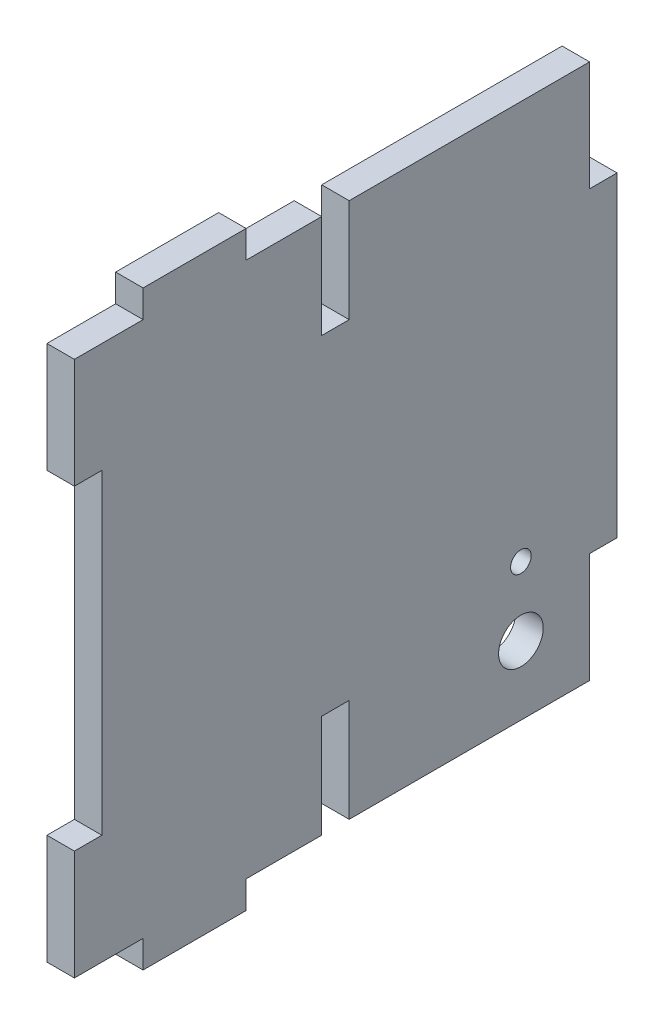
SolidWorks part; units mm, degrees
ref_plane "Front Plane" through (0, 0, 0) normal (0, 0, 1) x (1, 0, 0)
ref_plane "Top Plane" through (0, 0, 0) normal (0, 1, 0) x (1, 0, 0)
ref_plane "Right Plane" through (0, 0, 0) normal (1, 0, 0) x (0, 0, -1)
sketch "Sketch1" plane through (0, 0, 0) normal (1, 0, 0) x (0, 0, -1)
  line L0 (10, 0) -> (10, -4)
  line L1 (0, 0) -> (10, 0)
  line L2 (0, 0) -> (0, 16)
  line L3 (0, 78) -> (10, 78)
  line L4 (75, 0) -> (75, 16)
  line L5 (10, -4) -> (25, -4)
  line L6 (25, -4) -> (25, 0)
  line L7 (25, 0) -> (36, 0)
  line L8 (10, 78) -> (10, 82)
  line L9 (40, 78) -> (75, 78)
  line L10 (40, 0) -> (75, 0)
  line L11 (36, 78) -> (36, 63)
  line L12 (36, 63) -> (40, 63)
  line L13 (10, 82) -> (25, 82)
  line L14 (25, 82) -> (25, 78)
  line L15 (25, 78) -> (36, 78)
  line L16 (40, 78) -> (40, 63)
  line L17 (75, 62) -> (75, 78)
  line L18 (36, 0) -> (36, 15)
  line L19 (36, 15) -> (40, 15)
  line L20 (40, 0) -> (40, 15)
  line L21 (75, 62) -> (79, 62)
  line L22 (0, 62) -> (0, 78)
  line L23 (75, 16) -> (79, 16)
  line L24 (79, 62) -> (79, 16)
  line L25 (0, 62) -> (4, 62)
  line L27 (0, 16) -> (4, 16)
  line L28 (4, 62) -> (4, 16)
  point P25 (77, 16)
  dimension "D1" = 78
  dimension "D3" = 4
  dimension "D4" = 10
  dimension "D5" = 15
  dimension "D10" = 4
  dimension "D2" = 36
  dimension "D6" = 15
  dimension "D7" = 15
  dimension "D8" = 4
  dimension "D9" = 35
  dimension "D11" = 4
  dimension "D12" = 16
  dimension "D13" = 16
  dimension "D15" = 46
  dimension "D14" = 20
  dimension "D16" = 4
extrude "Boss-Extrude1" add sketch "Sketch1" along normal blind 4
sketch "Sketch2" plane through (4, 0, 0) normal (1, 0, 0) x (0, 0, -1)
  line L2 (25, 0) -> (36, 0) construction
  line L4 (75, 0) -> (75, 16) construction
  circle A0 centre (65, 10) radius 3.25
  circle A1 centre (65, 20) radius 1.5
  dimension "D2" = 6.5
  dimension "D4" = 3
  dimension "D5" = 10
  dimension "D1" = 10
  dimension "D3" = 10
extrude "Cut-Extrude1" cut sketch "Sketch2" against normal through all
equation "\"D10@Sketch1\"=\"D3@Sketch1\""
